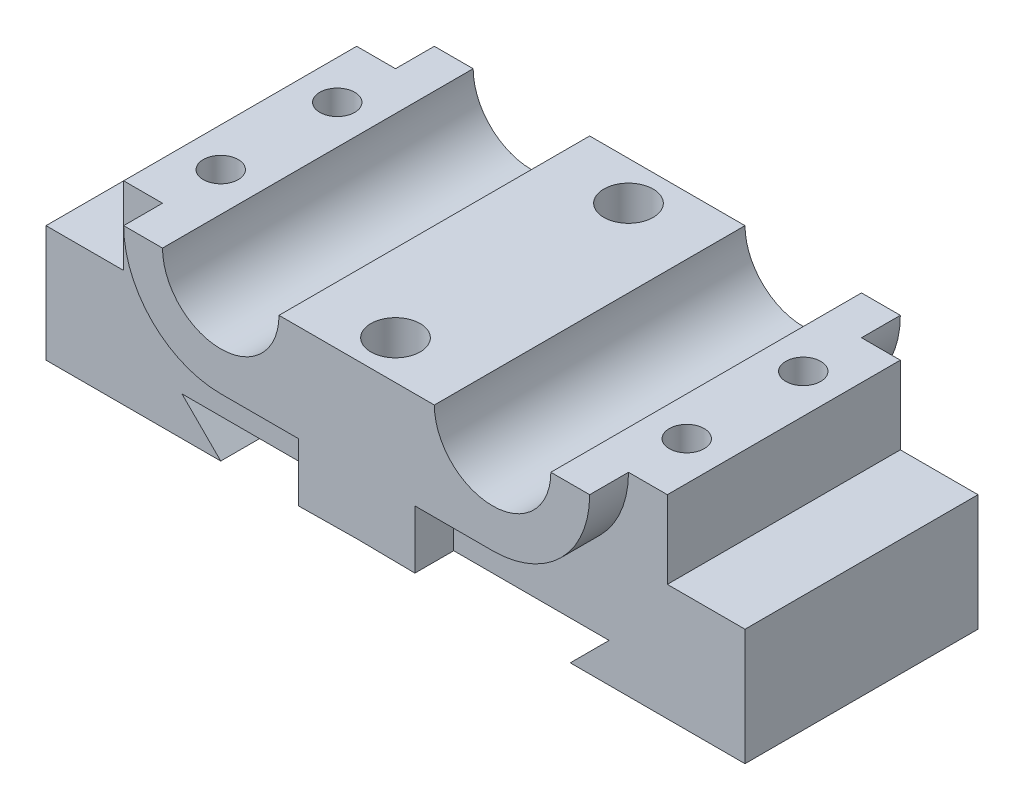
SolidWorks part; units mm, degrees
ref_plane "Front Plane" through (0, 0, 0) normal (0, 0, 1) x (1, 0, 0)
ref_plane "Top Plane" through (0, 0, 0) normal (0, 1, 0) x (1, 0, 0)
ref_plane "Right Plane" through (0, 0, 0) normal (1, 0, 0) x (0, 0, -1)
sketch "Sketch1" plane through (0, 0, 0) normal (0, 0, 1) x (1, 0, 0)
  line L0 (-45, 9.9065) -> (-45, -5.0935)
  line L1 (0, 0) -> (0, 16888.4449) construction
  line L2 (10, 19.9065) -> (-10, 19.9065)
  line L3 (-35, 19.9065) -> (-35, 9.9065)
  line L4 (-35, 9.9065) -> (-45, 9.9065)
  line L5 (-45, -5.0935) -> (-22.5, -5.0935)
  line L6 (-22.5, -5.0935) -> (-27.5, -0.0935)
  line L7 (-27.5, -0.0935) -> (27.5, -0.0935)
  line L8 (-25, 19.9065) -> (-35, 19.9065)
  line L9 (22.5, -5.0935) -> (27.5, -0.0935)
  line L10 (45, -5.0935) -> (22.5, -5.0935)
  line L11 (45, 9.9065) -> (45, -5.0935)
  line L12 (35, 9.9065) -> (45, 9.9065)
  line L13 (35, 19.9065) -> (35, 9.9065)
  line L14 (25, 19.9065) -> (35, 19.9065)
  arc A0 (10, 19.9065) -> (25, 19.9065) centre (17.5, 19.9065) ccw
  arc A1 (-10, 19.9065) -> (-25, 19.9065) centre (-17.5, 19.9065) cw
  point P0 (-33.75, -5.0935)
  point P14 (0, -0.0935)
  point P24 (0, 19.9065)
  dimension "D11" = 7.5
  dimension "D1" = 22.5
  dimension "D2" = 22.5
  dimension "D3" = 5
  dimension "D4" = 5
  dimension "D5" = 15
  dimension "D6" = 10
  dimension "D7" = 35
  dimension "D8" = 10
  dimension "D10" = 17.5
extrude "Boss-Extrude1" add sketch "Sketch1" along normal blind 30
sketch "Sketch2" plane through (0, 0, 30) normal (0, 0, 1) x (1, 0, 0)
  line L2 (-7.5, -0.0935) -> (0, 0)
  line L3 (-17.5, 7.4065) -> (-7.5, 7.4065)
  line L4 (-7.5, 7.4065) -> (-7.5, -0.0935)
  line L5 (-27.5, -0.0935) -> (27.5, -0.0935) construction
  line L6 (7.5, -0.0935) -> (0, 0)
  line L7 (7.5, 7.4065) -> (7.5, -0.0935)
  line L8 (17.5, 7.4065) -> (7.5, 7.4065)
  line L9 (-30, 19.9065) -> (-25, 19.9065)
  line L10 (-10, 19.9065) -> (10, 19.9065)
  line L11 (30, 19.9065) -> (25, 19.9065)
  line L12 (45, -5.0935) -> (45, 9.9065) construction
  line L13 (22.5, -5.0935) -> (45, -5.0935) construction
  arc A0 (-17.5527, 19.9065) -> (-17.5468, 19.9308) centre (-17.5, 19.9065) cw
  arc A1 (-30, 19.9065) -> (-17.5, 7.4065) centre (-17.5, 19.9065) ccw
  arc A2 (30, 19.9065) -> (17.5, 7.4065) centre (17.5, 19.9065) cw
  arc A3 (-25, 19.9065) -> (-10, 19.9065) centre (-17.5, 19.9065) ccw
  arc A4 (-25, 19.9065) -> (-10, 19.9065) centre (-17.5, 19.9065) ccw construction
  arc A5 (25, 19.9065) -> (10, 19.9065) centre (17.5, 19.9065) cw
  point P28 (0, 0)
  point P29 (17.5, 7.4065)
  point P30 (-17.5527, 7.4066)
  dimension "D1" = 25
  dimension "D2" = 7.5
extrude "Boss-Extrude2" add sketch "Sketch2" along normal blind 5 and the other way blind 35 contours L10 A5 L11 A2 L8 L7 L6 L2 L4 L3 A1 L9 A3
sketch "Sketch3" plane through (0, 19.9065, 0) normal (0, 1, 0) x (1, 0, 0)
  line L0 (0, 5) -> (0, -15) construction
  line L1 (-10, 5) -> (10, 5) construction
  line L2 (-35, -30) -> (-35, 0) construction
  line L3 (0, -15) -> (-35, -15) construction
  line L4 (-35, -30) -> (-35, 0) construction
  circle A0 centre (0, 0) radius 3.1739
  circle A1 centre (-30, -7.5) radius 2.25
  circle A2 centre (30, -7.5) radius 2.25
  circle A3 centre (30, -22.5) radius 2.25
  circle A4 centre (0, -30) radius 3.1739
  circle A5 centre (-30, -22.5) radius 2.25
  dimension "D1" = 4.5
  dimension "D2" = 7.5
  dimension "D3" = 5
extrude "Cut-Extrude1" cut sketch "Sketch3" against normal blind 15
